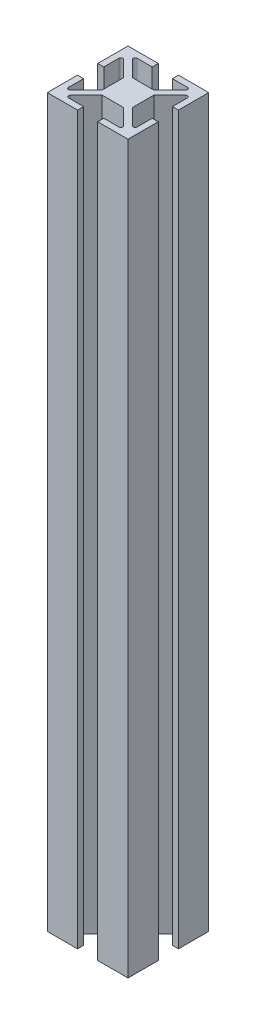
SolidWorks part; units mm, degrees
ref_plane "Plan de face" through (0, 0, 0) normal (0, 0, 1) x (1, 0, 0)
ref_plane "Plan de dessus" through (0, 0, 0) normal (0, 1, 0) x (1, 0, 0)
ref_plane "Plan de droite" through (0, 0, 0) normal (1, 0, 0) x (0, 0, -1)
sketch "Esquisse1" plane through (0, 0, 0) normal (0, 1, 0) x (1, 0, 0)
  line L0 (6.1245, 16.1036) -> (30.6226, 16.1036) construction
  line L6 (-11.5924, 0) -> (12.1076, 0) construction
  line L7 (0, 12.3466) -> (0, -12.7449) construction
  line L12 (-10, -10) -> (10, 10) construction
  line L59 (-10, -2.5) -> (-10, -10)
  line L60 (-10, -2.5) -> (-8.5, -2.5)
  line L69 (-8.5, -2.5) -> (-8.5, -6.2322)
  line L70 (-7.6464, -6.5858) -> (-3.75, -2.6893)
  line L73 (-6.5858, -7.6464) -> (-2.6893, -3.75)
  line L74 (-2.5, -8.5) -> (-6.2322, -8.5)
  line L75 (-2.5, -10) -> (-2.5, -8.5)
  line L76 (-2.5, -10) -> (-10, -10)
  line L77 (-2.5, 10) -> (-2.5, 8.5)
  line L78 (-2.5, 10) -> (-10, 10)
  line L79 (-10, 2.5) -> (-10, 10)
  line L80 (-10, 2.5) -> (-8.5, 2.5)
  line L81 (-8.5, 2.5) -> (-8.5, 6.2322)
  line L82 (-7.6464, 6.5858) -> (-3.75, 2.6893)
  line L83 (-6.5858, 7.6464) -> (-2.6893, 3.75)
  line L84 (-2.5, 8.5) -> (-6.2322, 8.5)
  line L85 (10, 2.5) -> (8.5, 2.5)
  line L86 (10, 2.5) -> (10, 10)
  line L87 (2.5, 10) -> (10, 10)
  line L88 (2.5, 10) -> (2.5, 8.5)
  line L89 (2.5, 8.5) -> (6.2322, 8.5)
  line L90 (6.5858, 7.6464) -> (2.6893, 3.75)
  line L91 (7.6464, 6.5858) -> (3.75, 2.6893)
  line L92 (8.5, 2.5) -> (8.5, 6.2322)
  line L93 (2.5, -10) -> (2.5, -8.5)
  line L94 (2.5, -10) -> (10, -10)
  line L95 (10, -2.5) -> (10, -10)
  line L96 (10, -2.5) -> (8.5, -2.5)
  line L97 (8.5, -2.5) -> (8.5, -6.2322)
  line L98 (7.6464, -6.5858) -> (3.75, -2.6893)
  line L99 (6.5858, -7.6464) -> (2.6893, -3.75)
  line L100 (2.5, -8.5) -> (6.2322, -8.5)
  line L101 (-3.75, 2.6893) -> (-3.75, -2.6893)
  line L102 (-2.6893, -3.75) -> (2.6893, -3.75)
  line L103 (-2.6893, 3.75) -> (2.6893, 3.75)
  line L104 (3.75, 2.6893) -> (3.75, -2.6893)
  arc A0 (-8.5, 6.2322) -> (-7.6464, 6.5858) centre (-8, 6.2322) cw
  arc A1 (-8.5, -6.2322) -> (-7.6464, -6.5858) centre (-8, -6.2322) ccw
  arc A2 (-6.5858, -7.6464) -> (-6.2322, -8.5) centre (-6.2322, -8) ccw
  arc A3 (6.5858, -7.6464) -> (6.2322, -8.5) centre (6.2322, -8) cw
  arc A4 (8.5, -6.2322) -> (7.6464, -6.5858) centre (8, -6.2322) cw
  arc A5 (7.6464, 6.5858) -> (8.5, 6.2322) centre (8, 6.2322) cw
  arc A6 (6.2322, 8.5) -> (6.5858, 7.6464) centre (6.2322, 8) cw
  arc A7 (-6.5858, 7.6464) -> (-6.2322, 8.5) centre (-6.2322, 8) cw
  point P7 (-2.5, -9.25)
  point P8 (2.5, -9.25)
  point P15 (-8.5, -7.4393)
  point P51 (0, 0)
  point P52 (-7.4393, -8.5)
  dimension "D2" = 5
  dimension "D7" = 0.5
  dimension "D1" = 20
  dimension "D3" = 4
  dimension "D4" = 7.5
  dimension "D5" = 1.5
  dimension "D6" = 1.5
extrude "Boss.-Extru.1" add sketch "Esquisse1" along normal blind 180
